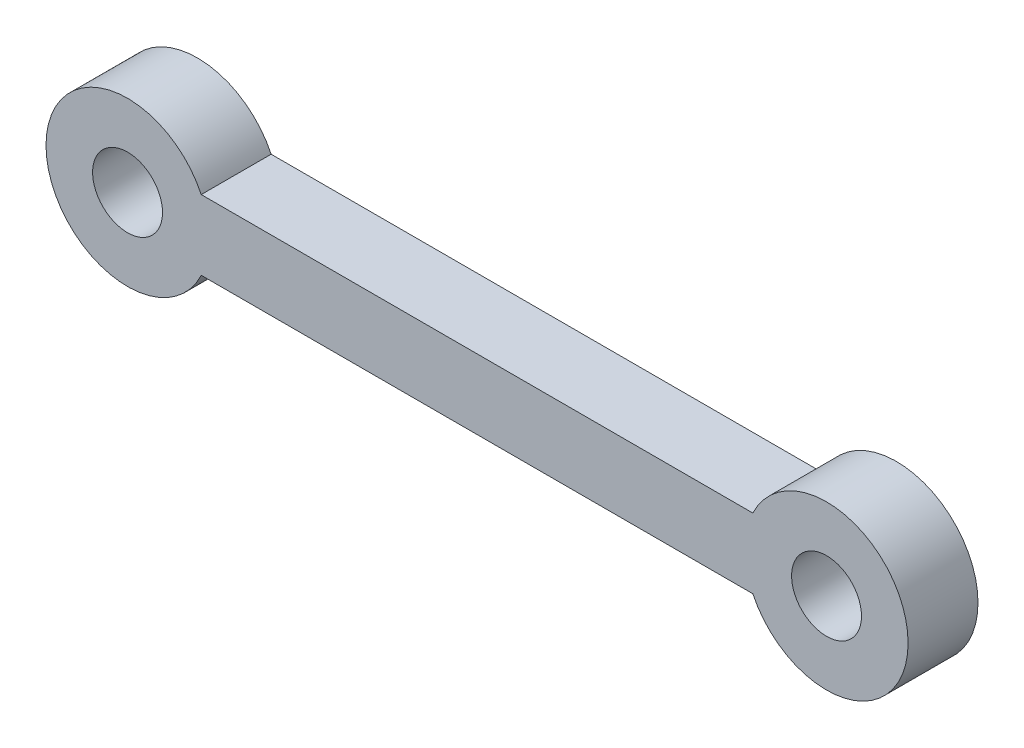
SolidWorks part; units mm, degrees
material "普通碳钢"
ref_plane "前视" through (0, 0, 0) normal (0, 0, 1) x (1, 0, 0)
ref_plane "上视" through (0, 0, 0) normal (0, 1, 0) x (1, 0, 0)
ref_plane "右视" through (0, 0, 0) normal (1, 0, 0) x (0, 0, -1)
sketch "草图1" plane through (0, 0, 0) normal (0, 0, 1) x (1, 0, 0)
  line L0 (0, 0) -> (30, 0) construction
  line L1 (3.1623, 1.5) -> (26.8377, 1.5)
  line L2 (3.1623, -1.5) -> (26.8377, -1.5)
  arc A0 (3.1623, 1.5) -> (3.1623, -1.5) centre (0, 0) ccw
  arc A1 (26.8377, -1.5) -> (26.8377, 1.5) centre (30, 0) ccw
  circle A2 centre (0, 0) radius 1.5
  circle A3 centre (30, 0) radius 1.5
  dimension "D1" = 7
  dimension "D4" = 3
  dimension "D2" = 3
  dimension "D3" = 30
extrude "凸台-拉伸1" add sketch "草图1" along normal blind 3
